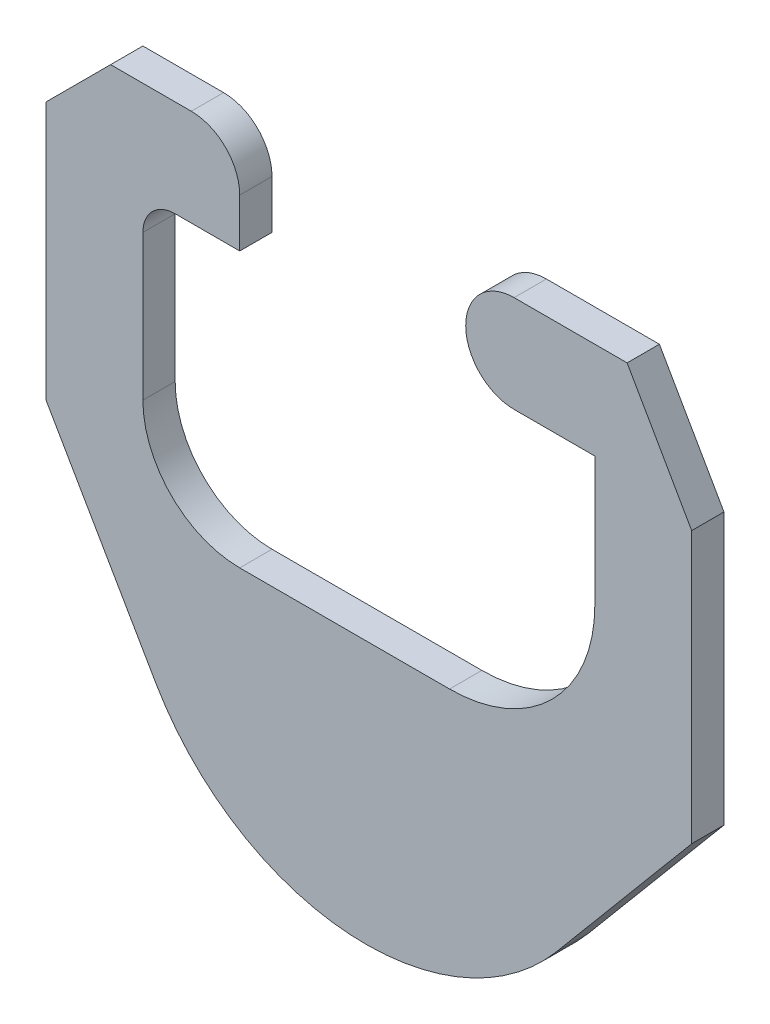
SolidWorks part; units mm, degrees
material "Plain Carbon Steel"
ref_plane "Front Plane" through (0, 0, 0) normal (0, 0, 1) x (1, 0, 0)
ref_plane "Top Plane" through (0, 0, 0) normal (0, 1, 0) x (1, 0, 0)
ref_plane "Right Plane" through (0, 0, 0) normal (1, 0, 0) x (0, 0, -1)
sketch "Sketch1" plane through (0, 0, 0) normal (0, 0, 1) x (1, 0, 0)
  line L0 (0, 0) -> (35, 0)
  line L1 (35, 0) -> (55, -35)
  line L2 (55, -35) -> (55, -119)
  line L5 (-145, -100) -> (-145, -20)
  line L6 (-145, -20) -> (-125, 0)
  line L7 (-125, 0) -> (-100, 0)
  line L8 (-85, -15) -> (-85, -30)
  line L9 (-85, -30) -> (-105, -30)
  line L10 (-115, -40) -> (-115, -85)
  line L11 (-85, -115) -> (-20, -115)
  line L12 (25, -70) -> (25, -30)
  line L13 (25, -30) -> (0, -30)
  line L14 (-145, -100) -> (-110.9751, -158.9328)
  line L15 (13.2188, -168.7929) -> (55, -119)
  arc A0 (-100, 0) -> (-85, -15) centre (-100, -15) cw
  arc A1 (-105, -30) -> (-115, -40) centre (-105, -40) ccw
  arc A4 (-115, -85) -> (-85, -115) centre (-85, -85) ccw
  arc A5 (-20, -115) -> (25, -70) centre (-20, -70) ccw
  arc A6 (0, -30) -> (0, 0) centre (0, -15) cw
  arc A9 (-110.9751, -158.9328) -> (-45, -196.4258) centre (-46.0232, -121.4328) ccw
  arc A10 (-45, -196.4258) -> (13.2188, -168.7929) centre (-46.0557, -119.0557) ccw
  dimension "D2" = 15
  dimension "D7" = 45
  dimension "D14" = 15
  dimension "D4" = 10
  dimension "D6" = 20
  dimension "D21" = 75
  dimension "D1" = 85
  dimension "D3" = 35
  dimension "D5" = 65
  dimension "D8" = 30
  dimension "D9" = 30
  dimension "D10" = 20
  dimension "D11" = 80
  dimension "D12" = 45
  dimension "D13" = 30
  dimension "D15" = 60
  dimension "D16" = 84
  dimension "D17" = 55
  dimension "D18" = 30
  dimension "D19" = 15
  dimension "D20" = 100
  dimension "D22" = 65
  dimension "D23" = 220
extrude "Boss-Extrude1" add sketch "Sketch1" along normal blind 10
